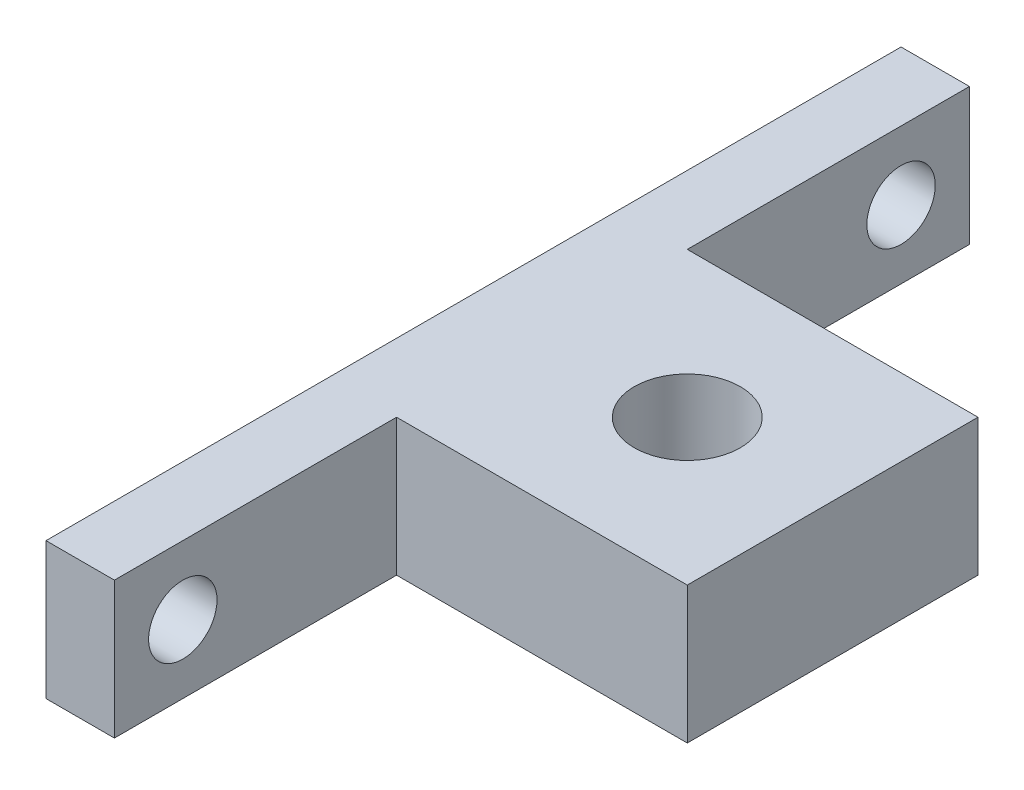
SolidWorks part; units mm, degrees
ref_plane "前视基准面" through (0, 0, 0) normal (0, 0, 1) x (1, 0, 0)
ref_plane "上视基准面" through (0, 0, 0) normal (0, 1, 0) x (1, 0, 0)
ref_plane "右视基准面" through (0, 0, 0) normal (1, 0, 0) x (0, 0, -1)
sketch "草图1" plane through (0, 0, 0) normal (1, 0, 0) x (0, 0, -1)
  line L0 (0, 4) -> (0, -4) construction
  line L1 (-25, -4) -> (25, -4)
  line L2 (-25, -4) -> (-25, 4)
  line L3 (-25, 4) -> (25, 4)
  line L4 (25, -4) -> (25, 4)
  line L5 (-25, -4) -> (25, 4) construction
  line L6 (-25, 4) -> (25, -4) construction
  circle A0 centre (-21, 0) radius 2
  circle A1 centre (21, 0) radius 2
  point P0 (0, 0)
  dimension "D3" = 4
  dimension "D1" = 50
  dimension "D2" = 8
  dimension "D4" = 4
extrude "凸台-拉伸1" add sketch "草图1" along normal blind 4
sketch "草图2" plane through (4, 0, 0) normal (1, 0, 0) x (0, 0, -1)
  line L0 (25, 4) -> (-25, 4) construction
  line L1 (8.5, -4) -> (-8.5, -4)
  line L2 (8.5, -4) -> (8.5, 4)
  line L3 (8.5, 4) -> (-8.5, 4)
  line L4 (-8.5, -4) -> (-8.5, 4)
  line L5 (8.5, -4) -> (-8.5, 4) construction
  line L6 (8.5, 4) -> (-8.5, -4) construction
  point P0 (0, 0)
  dimension "D1" = 17
extrude "凸台-拉伸2" add sketch "草图2" along normal blind 17
sketch "草图3" plane through (0, -4, 0) normal (0, -1, 0) x (1, 0, 0)
  line L0 (14, 7) -> (14, 6.6) construction
  line L1 (14, -6.6) -> (14, -7) construction
  line L2 (12.5, 8.5) -> (12.5, -8.5) construction
  line L3 (21, 8.5) -> (4, 8.5) construction
  line L4 (0, 25) -> (0, -25) construction
  line L5 (21, 8.5) -> (21, -8.5) construction
  line L6 (21, -8.5) -> (4, -8.5) construction
  circle A2 centre (12.5, 0) radius 3.1
  dimension "D1" = 6.2
  dimension "D2" = 14
  dimension "D3" = 7
extrude "切除-拉伸1" cut sketch "草图3" against normal through all
